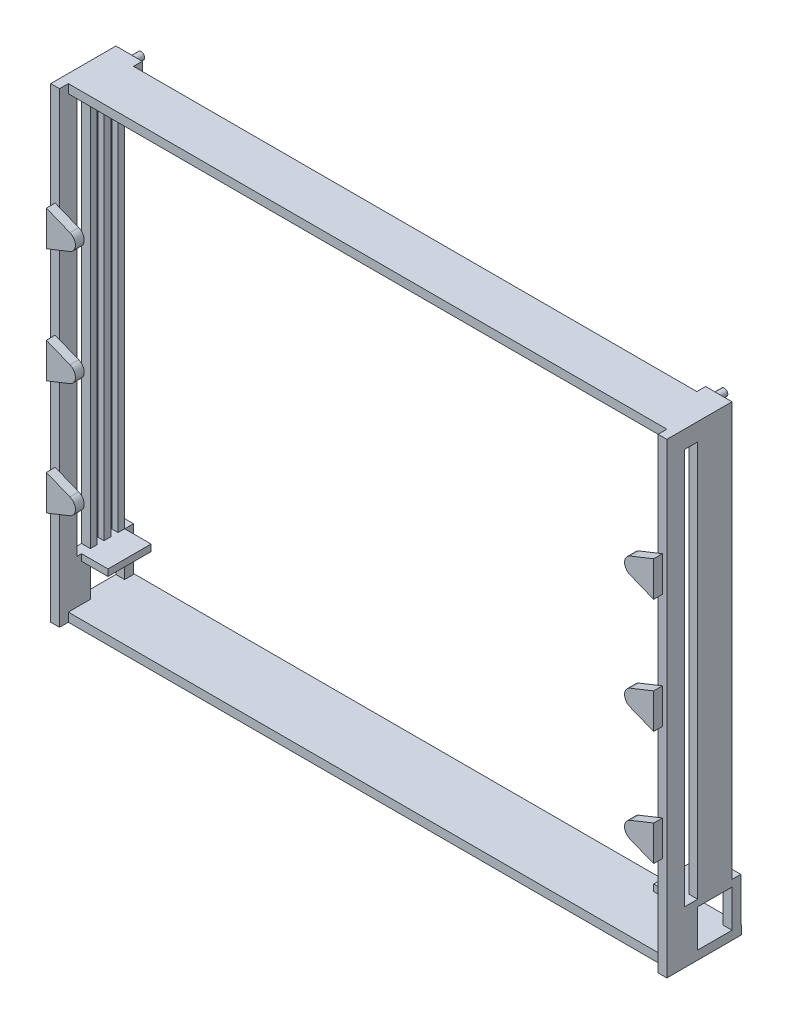
SolidWorks part; units mm, degrees
ref_plane "Plan de face" through (0, 0, 0) normal (0, 0, 1) x (1, 0, 0)
ref_plane "Plan de dessus" through (0, 0, 0) normal (0, 1, 0) x (1, 0, 0)
ref_plane "Plan de droite" through (0, 0, 0) normal (1, 0, 0) x (0, 0, -1)
sketch "Esquisse1" plane through (0, 0, 0) normal (0, 1, 0) x (1, 0, 0)
  line L0 (10, 0) -> (690, 0) construction
  line L1 (0, 0) -> (10, 0)
  line L2 (0, 0) -> (0, 25)
  line L3 (0, 25) -> (10, 25)
  line L4 (10, 0) -> (10, 25)
  line L6 (690, 0) -> (700, 0)
  line L7 (690, 0) -> (690, 25)
  line L8 (690, 25) -> (700, 25)
  line L9 (700, 0) -> (700, 25)
  dimension "D1" = 680
  dimension "D2" = 10
  dimension "D3" = 25
  dimension "D4" = 10
  dimension "D5" = 25
extrude "Boss.-Extru.1" add sketch "Esquisse1" along normal blind 530
sketch "Esquisse7" plane through (0, 0, 0) normal (0, 0, 1) x (1, 0, 0)
  line L0 (5, 530) -> (5, 415) construction
  line L1 (0, 530) -> (10, 530) construction
  line L2 (5, 415) -> (5, 375) construction
  line L3 (5, 375) -> (5, 285) construction
  line L4 (5, 415) -> (55, 395)
  line L5 (55, 395) -> (5, 375)
  line L6 (5, 375) -> (5, 415)
  line L7 (5, 285) -> (5, 245) construction
  line L8 (5, 245) -> (5, 155) construction
  line L9 (5, 155) -> (5, 115) construction
  line L10 (615, 395) -> (5, 395) construction
  line L11 (5, 285) -> (55, 265)
  line L12 (55, 265) -> (5, 245)
  line L13 (5, 245) -> (5, 285)
  line L14 (5, 155) -> (55, 135)
  line L15 (55, 135) -> (5, 115)
  line L16 (5, 115) -> (5, 155)
  line L17 (615, 460) -> (615, 330) construction
  line L18 (615, 330) -> (615, 200) construction
  line L19 (615, 265) -> (5, 265) construction
  line L20 (615, 200) -> (615, 70) construction
  line L21 (615, 135) -> (5, 135) construction
  line L23 (10, 530) -> (690, 530) construction
  line L24 (350, 530) -> (350, 0) construction
  line L25 (85, 135) -> (695, 135) construction
  line L26 (85, 265) -> (695, 265) construction
  line L27 (85, 330) -> (85, 200) construction
  line L28 (85, 395) -> (695, 395) construction
  line L29 (695, 155) -> (695, 115) construction
  line L30 (695, 245) -> (695, 155) construction
  line L31 (695, 285) -> (695, 245) construction
  line L32 (695, 375) -> (695, 285) construction
  line L33 (695, 415) -> (695, 375) construction
  line L34 (695, 115) -> (695, 155)
  line L35 (645, 135) -> (695, 115)
  line L36 (695, 155) -> (645, 135)
  line L37 (695, 245) -> (695, 285)
  line L38 (645, 265) -> (695, 245)
  line L39 (695, 285) -> (645, 265)
  line L40 (695, 375) -> (695, 415)
  line L41 (645, 395) -> (695, 375)
  line L42 (695, 415) -> (645, 395)
  dimension "D1" = 20
  dimension "D2" = 50
  dimension "D3" = 20
  dimension "D4" = 20
  dimension "D5" = 20
  dimension "D6" = 50
  dimension "D7" = 20
  dimension "D8" = 20
  dimension "D9" = 50
extrude "Boss.-Extru.4" add sketch "Esquisse7" along normal blind 10
sketch "Esquisse8" plane through (0, 0, -25) normal (0, 0, -1) x (-1, 0, 0)
  line L0 (-10, 530) -> (-10, 0) construction
  line L1 (0, 0) -> (-10, 0)
  line L2 (0, 0) -> (0, 10)
  line L3 (0, 10) -> (-10, 10)
  line L4 (-10, 0) -> (-10, 10)
  dimension "D1" = 10
extrude "Boss.-Extru.5" add sketch "Esquisse8" along normal blind 60
sketch "Esquisse9" plane through (10, 0, 0) normal (1, 0, 0) x (0, 0, -1)
  line L0 (0, 0) -> (85, 0) construction
  line L1 (85, 10) -> (25, 10)
  line L2 (85, 10) -> (85, 0)
  line L3 (85, 0) -> (25, 0)
  line L4 (25, 10) -> (25, 0)
  line L5 (25, 530) -> (25, 0) construction
extrude "Boss.-Extru.6" add sketch "Esquisse9" along normal blind 690
fillet "Congé1" radius 10 3 edges at (55, 395, 5) (55, 135, 5) (55, 265, 5)
fillet "Congé2" radius 10 1 edges at (645, 395, 5)
fillet "Congé3" radius 10 1 edges at (645, 265, 5)
fillet "Congé4" radius 10 1 edges at (645, 135, 5)
sketch "Esquisse10" plane through (0, 0, -25) normal (0, 0, 1) x (1, 0, 0)
  line L1 (10, 0) -> (690, 0)
  line L2 (10, 0) -> (10, 10)
  line L3 (10, 10) -> (690, 10)
  line L4 (690, 0) -> (690, 10)
extrude "Boss.-Extru.7" add sketch "Esquisse10" along normal blind 15
sketch "Esquisse11" plane through (0, 0, -25) normal (0, 0, -1) x (-1, 0, 0)
  line L0 (-690, 530) -> (-690, 10) construction
  line L1 (-700, 10) -> (-690, 10)
  line L2 (-700, 10) -> (-700, 60)
  line L3 (-700, 60) -> (-690, 60)
  line L4 (-690, 10) -> (-690, 60)
  line L5 (-350, 10) -> (-350, 457.7325) construction
  line L6 (-700, 10) -> (0, 10) construction
  line L7 (0, 60) -> (-10, 60)
  line L8 (-10, 10) -> (-10, 60)
  line L9 (0, 10) -> (-10, 10)
  line L10 (0, 10) -> (0, 60)
  dimension "D1" = 50
extrude "Boss.-Extru.8" add sketch "Esquisse11" along normal blind 10
sketch "Esquisse12" plane through (0, 0, -35) normal (0, 0, -1) x (-1, 0, 0)
  line L0 (-690, 10) -> (-690, 60) construction
  line L1 (-700, 60) -> (-690, 60)
  line L2 (-700, 60) -> (-700, 52.5)
  line L3 (-700, 52.5) -> (-690, 52.5)
  line L4 (-690, 60) -> (-690, 52.5)
  line L5 (-350, 10) -> (-350, 481.8712) construction
  line L6 (-700, 10) -> (0, 10) construction
  line L11 (-10, 60) -> (-10, 52.5)
  line L12 (0, 52.5) -> (-10, 52.5)
  line L13 (0, 60) -> (0, 52.5)
  line L14 (0, 60) -> (-10, 60)
  dimension "D1" = 7.5
extrude "Boss.-Extru.9" add sketch "Esquisse12" along normal blind 39
sketch "Esquisse13" plane through (690, 0, 0) normal (-1, 0, 0) x (0, 0, 1)
  line L1 (-25, 60) -> (-74, 60)
  line L2 (-25, 60) -> (-25, 52.5)
  line L3 (-25, 52.5) -> (-74, 52.5)
  line L4 (-74, 60) -> (-74, 52.5)
extrude "Boss.-Extru.10" add sketch "Esquisse13" along normal blind 30
sketch "Esquisse19" plane through (10, 0, 0) normal (1, 0, 0) x (0, 0, -1)
  line L1 (25, 60) -> (74, 60)
  line L2 (25, 60) -> (25, 52.5)
  line L3 (25, 52.5) -> (74, 52.5)
  line L4 (74, 60) -> (74, 52.5)
extrude "Boss.-Extru.14" add sketch "Esquisse19" along normal blind 30
sketch "Esquisse14" plane through (0, 60, 0) normal (0, 1, 0) x (1, 0, 0)
  line L0 (350, 85) -> (350, -100.166) construction
  line L1 (690, 25) -> (700, 25)
  line L2 (690, 25) -> (690, 74)
  line L3 (690, 74) -> (700, 74)
  line L4 (700, 25) -> (700, 74)
  line L5 (700, 85) -> (0, 85) construction
  line L6 (0, 25) -> (0, 74)
  line L7 (10, 74) -> (0, 74)
  line L8 (10, 25) -> (10, 74)
  line L9 (10, 25) -> (0, 25)
extrude "Boss.-Extru.11" add sketch "Esquisse14" along normal blind 470
sketch "Esquisse16" plane through (690, 0, 0) normal (-1, 0, 0) x (0, 0, 1)
  line L1 (-74, 530) -> (-64, 530)
  line L2 (-74, 530) -> (-74, 520)
  line L3 (-74, 520) -> (-64, 520)
  line L4 (-64, 530) -> (-64, 520)
  dimension "D1" = 10
  dimension "D2" = 10
extrude "Boss.-Extru.12" add sketch "Esquisse16" along normal blind 20
sketch "Esquisse20" plane through (10, 0, 0) normal (1, 0, 0) x (0, 0, -1)
  line L1 (74, 530) -> (64, 530)
  line L2 (74, 530) -> (74, 520)
  line L3 (74, 520) -> (64, 520)
  line L4 (64, 530) -> (64, 520)
  dimension "D1" = 10
  dimension "D2" = 10
extrude "Boss.-Extru.15" add sketch "Esquisse20" along normal blind 20
sketch "Esquisse17" plane through (0, 0, -74) normal (0, 0, -1) x (-1, 0, 0)
  line L0 (-700, 525) -> (-685, 525) construction
  line L3 (-700, 530) -> (-700, 52.5) construction
  line L4 (-685, 525) -> (-677.5, 525) construction
  line L5 (-350, 10) -> (-350, 469.8018) construction
  line L6 (-700, 10) -> (0, 10) construction
  line L7 (-15, 525) -> (-22.5, 525) construction
  line L8 (0, 525) -> (-15, 525) construction
  circle A0 centre (-681.25, 525) radius 4
  circle A1 centre (-18.75, 525) radius 4
  dimension "D3" = 8
  dimension "D1" = 15
  dimension "D2" = 7.5
extrude "Boss.-Extru.13" add sketch "Esquisse17" along normal blind 10
sketch "Esquisse21" plane through (10, 0, 0) normal (1, 0, 0) x (0, 0, -1)
  line L0 (0, 530) -> (64, 530) construction
  line L1 (64, 520) -> (10, 520)
  line L2 (64, 520) -> (64, 530)
  line L3 (64, 530) -> (10, 530)
  line L4 (10, 520) -> (10, 530)
  dimension "D1" = 54
extrude "Boss.-Extru.16" add sketch "Esquisse21" along normal up to next
sketch "Esquisse22" plane through (690, 0, 0) normal (-1, 0, 0) x (0, 0, 1)
  line L0 (-74, 530) -> (-20, 530) construction
  line L1 (-74, 530) -> (0, 530) construction
  line L2 (-20, 530) -> (-20, 0) construction
  line L3 (-85, 0) -> (0, 0) construction
  line L4 (-20, 510) -> (-35, 510) construction
  line L5 (-35, 510) -> (-35, 530) construction
  line L8 (-35, 510) -> (-20, 510)
  line L9 (-35, 510) -> (-35, 60)
  line L10 (-35, 60) -> (-20, 60)
  line L11 (-20, 510) -> (-20, 60)
  dimension "D1" = 54
  dimension "D2" = 15
  dimension "D3" = 20
  dimension "D4" = 450
extrude "Enlèv. mat.-Extru.1" cut sketch "Esquisse22" against normal through all both and the other way through all
sketch "Esquisse23" plane through (0, 0, -74) normal (0, 0, -1) x (-1, 0, 0)
  line L1 (-700, 52.5) -> (-690, 52.5)
  line L2 (-700, 52.5) -> (-700, 60)
  line L3 (-700, 60) -> (-690, 60)
  line L4 (-690, 52.5) -> (-690, 60)
extrude "Boss.-Extru.17" add sketch "Esquisse23" along normal blind 10
sketch "Esquisse24" plane through (0, 52.5, 0) normal (0, -1, 0) x (1, 0, 0)
  line L1 (690, -74) -> (700, -74)
  line L2 (690, -74) -> (690, -84)
  line L3 (690, -84) -> (700, -84)
  line L4 (700, -74) -> (700, -84)
extrude "Boss.-Extru.18" add sketch "Esquisse24" along normal through all contours L2 L1 L4 L3
sketch "Esquisse25" plane through (0, 0, -74) normal (0, 0, -1) x (-1, 0, 0)
  line L1 (-10, 60) -> (0, 60)
  line L2 (-10, 60) -> (-10, 52.5)
  line L3 (-10, 52.5) -> (0, 52.5)
  line L4 (0, 60) -> (0, 52.5)
extrude "Boss.-Extru.19" add sketch "Esquisse25" along normal blind 10
sketch "Esquisse26" plane through (0, 52.5, 0) normal (0, -1, 0) x (1, 0, 0)
  line L1 (10, -74) -> (0, -74)
  line L2 (10, -74) -> (10, -84)
  line L3 (10, -84) -> (0, -84)
  line L4 (0, -74) -> (0, -84)
extrude "Boss.-Extru.20" add sketch "Esquisse26" along normal through all
sketch "Esquisse28" plane through (690, 0, 0) normal (-1, 0, 0) x (0, 0, 1)
  line L0 (-35, 510) -> (-42.5, 510) construction
  line L1 (-42.5, 510) -> (-50.5, 510) construction
  line L2 (-50.5, 510) -> (-58.5, 510) construction
  line L3 (-58.5, 510) -> (-66.5, 510) construction
  line L4 (-66.5, 510) -> (-74, 510) construction
  line L5 (-74, 60) -> (-74, 530) construction
  line L6 (-35, 60) -> (-74, 60) construction
  line L8 (-66.5, 510) -> (-58.5, 510)
  line L9 (-66.5, 510) -> (-66.5, 60)
  line L10 (-66.5, 60) -> (-58.5, 60)
  line L11 (-58.5, 510) -> (-58.5, 60)
  line L12 (-50.5, 60) -> (-42.5, 60)
  line L13 (-50.5, 60) -> (-50.5, 510)
  line L14 (-50.5, 510) -> (-42.5, 510)
  line L15 (-42.5, 60) -> (-42.5, 510)
  dimension "D1" = 7.5
  dimension "D2" = 8
  dimension "D3" = 8
  dimension "D4" = 7.5
extrude "Enlèv. mat.-Extru.2" cut sketch "Esquisse28" against normal blind 7
sketch "Esquisse29" plane through (10, 0, 0) normal (1, 0, 0) x (0, 0, -1)
  line L0 (35, 510) -> (42.5, 510) construction
  line L1 (42.5, 510) -> (50.5, 510) construction
  line L2 (50.5, 510) -> (58.5, 510) construction
  line L3 (58.5, 510) -> (66.5, 510) construction
  line L4 (66.5, 510) -> (74, 510) construction
  line L5 (74, 530) -> (74, 60) construction
  line L6 (35, 60) -> (74, 60) construction
  line L8 (42.5, 60) -> (50.5, 60)
  line L9 (42.5, 60) -> (42.5, 510)
  line L10 (42.5, 510) -> (50.5, 510)
  line L11 (50.5, 60) -> (50.5, 510)
  line L12 (58.5, 510) -> (66.5, 510)
  line L13 (58.5, 510) -> (58.5, 60)
  line L14 (58.5, 60) -> (66.5, 60)
  line L15 (66.5, 510) -> (66.5, 60)
  dimension "D1" = 7.5
  dimension "D2" = 8
  dimension "D3" = 7.5
  dimension "D4" = 8
extrude "Enlèv. mat.-Extru.3" cut sketch "Esquisse29" against normal blind 7
equation "\".47.00cm\"=47"
